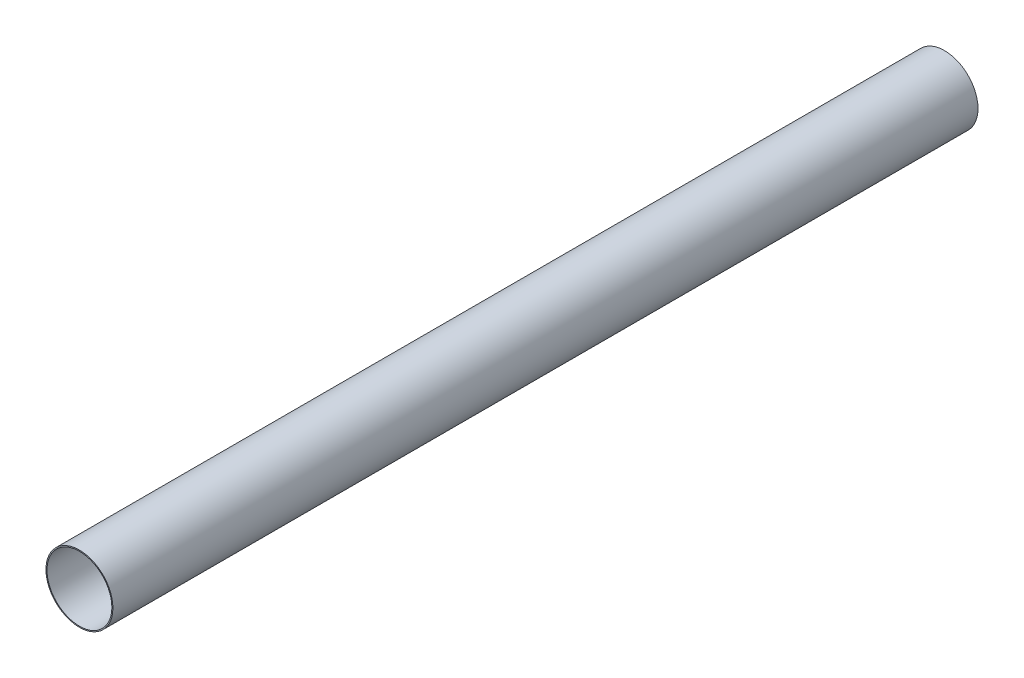
SolidWorks part; units mm, degrees
ref_plane "Front Plane" through (0, 0, 0) normal (0, 0, 1) x (1, 0, 0)
ref_plane "Top Plane" through (0, 0, 0) normal (0, 1, 0) x (1, 0, 0)
ref_plane "Right Plane" through (0, 0, 0) normal (1, 0, 0) x (0, 0, -1)
sketch "Sketch1" plane through (0, 0, 0) normal (0, 0, 1) x (1, 0, 0)
  circle A0 centre (0, 0) radius 51.1175
  circle A1 centre (0, 0) radius 49.53
  dimension "D1" = 102.235
  dimension "D2" = 1.5875
extrude "Boss-Extrude1" add sketch "Sketch1" along normal blind 1320.8
